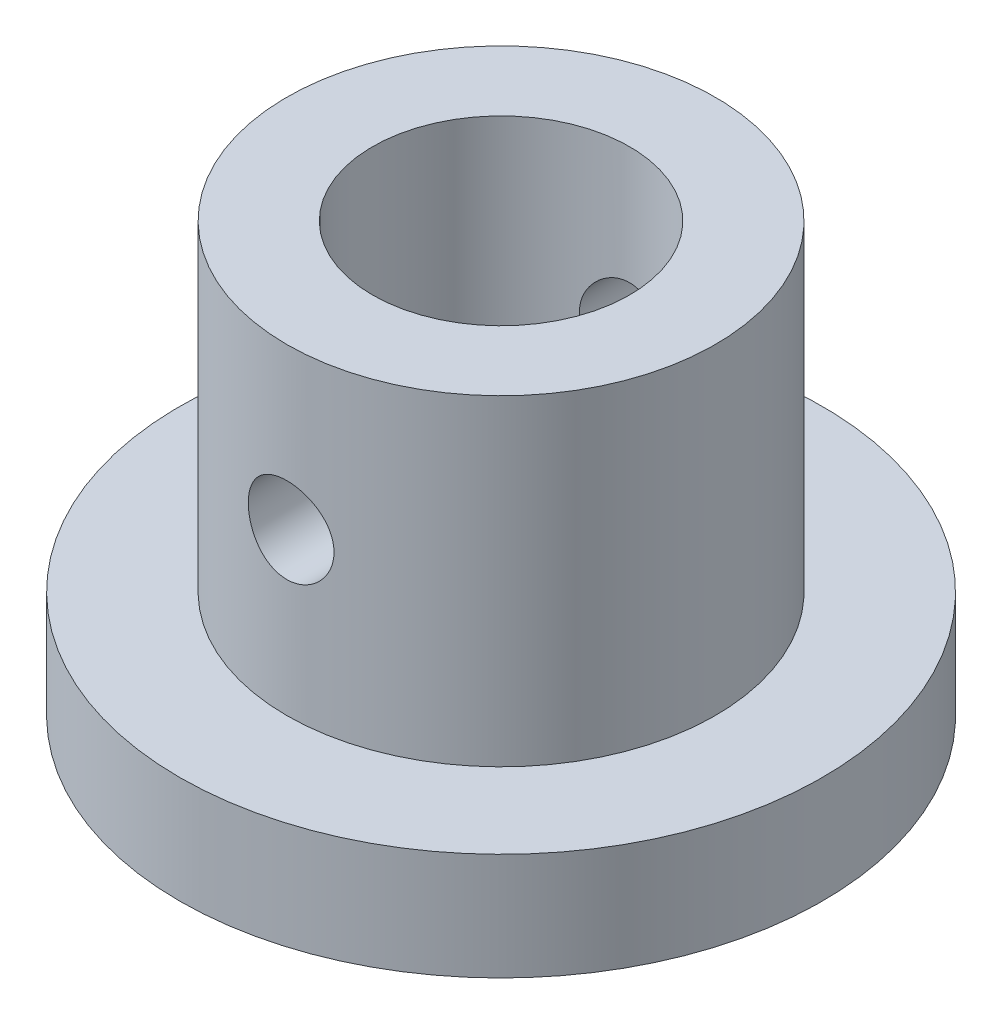
SolidWorks part; units mm, degrees
ref_plane "Ön Düzlem" through (0, 0, 0) normal (0, 0, 1) x (1, 0, 0)
ref_plane "Üst Düzlem" through (0, 0, 0) normal (0, 1, 0) x (1, 0, 0)
ref_plane "Sağ Düzlem" through (0, 0, 0) normal (1, 0, 0) x (0, 0, -1)
sketch "Çizim1" plane through (0, 0, 0) normal (0, 1, 0) x (1, 0, 0)
  circle A0 centre (0, 0) radius 150
  dimension "D1" = 300
extrude "Yükseklik-Ekstrüzyon2" add sketch "Çizim1" along normal blind 50
sketch "Çizim2" plane through (0, 50, 0) normal (0, 1, 0) x (1, 0, 0)
  circle A0 centre (0, 0) radius 100
  dimension "D1" = 200
extrude "Yükseklik-Ekstrüzyon3" add sketch "Çizim2" along normal blind 150
sketch "Çizim3" plane through (0, 200, 0) normal (0, 1, 0) x (1, 0, 0)
  circle A0 centre (0, 0) radius 60
  dimension "D1" = 120
extrude "Kes-Ekstrüzyon1" cut sketch "Çizim3" against normal through all
sketch "Çizim4" plane through (0, 0, 0) normal (0, 0, 1) x (1, 0, 0)
  line L0 (100, 200) -> (-100, 200) construction
  circle A0 centre (0, 125) radius 20
  dimension "D1" = 40
  dimension "D2" = 75
extrude "Kes-Ekstrüzyon2" cut sketch "Çizim4" against normal mid plane 260
